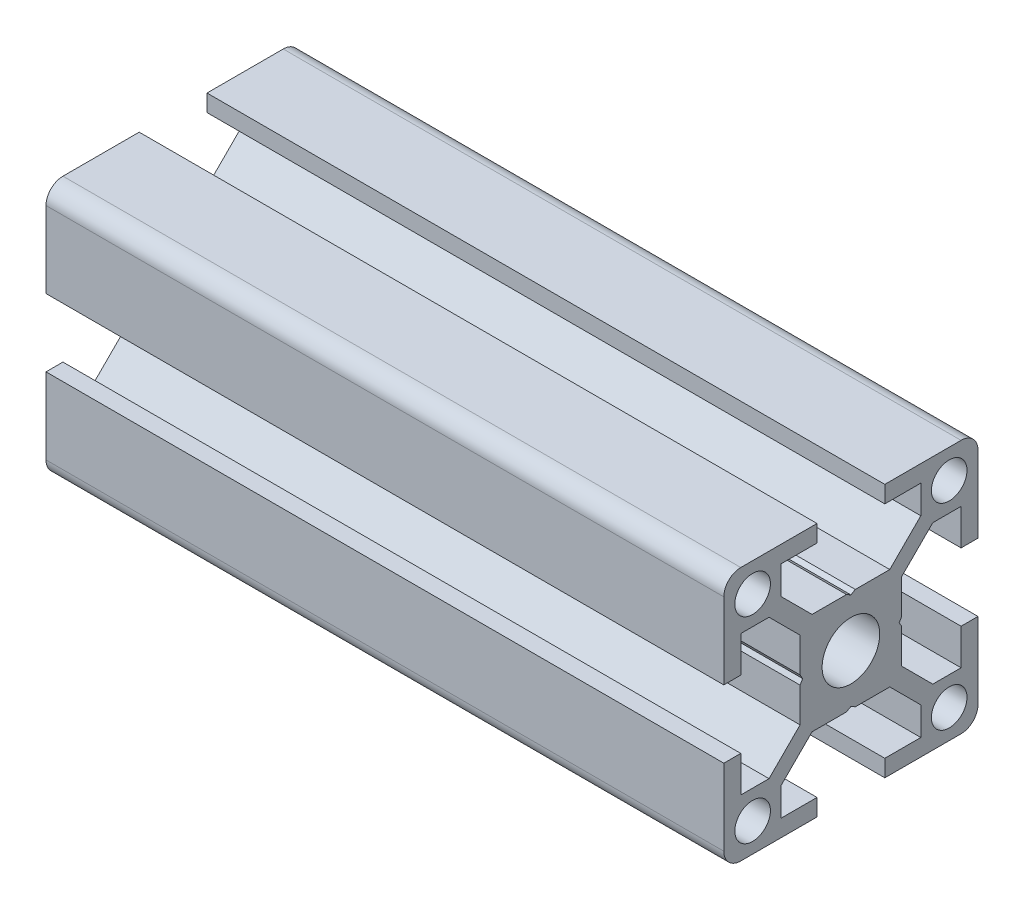
SolidWorks part; units mm, degrees
ref_plane "Front Plane" through (0, 0, 0) normal (0, 0, 1) x (1, 0, 0)
ref_plane "Top Plane" through (0, 0, 0) normal (0, 1, 0) x (1, 0, 0)
ref_plane "Right Plane" through (0, 0, 0) normal (1, 0, 0) x (0, 0, -1)
ref_plane "Plane1" through (0, 0, 0) normal (-1, 0, 0) x (0, -1, 0)
sketch "Sketch1" plane through (0, 0, 0) normal (-1, 0, 0) x (0, -1, 0)
  line L0 (13, -4) -> (13, -8.25)
  line L1 (13, -8.25) -> (9.6642, -8.25)
  line L2 (9.6642, -8.25) -> (6, -4.5858)
  line L3 (6, -4.5858) -> (6, -0.5196)
  line L4 (6, -0.5196) -> (5.7, 0)
  line L5 (5.7, 0) -> (6, 0.5196)
  line L6 (6, 0.5196) -> (6, 4.5858)
  line L7 (6, 4.5858) -> (9.6642, 8.25)
  line L8 (9.6642, 8.25) -> (13, 8.25)
  line L9 (13, 8.25) -> (13, 4)
  line L10 (13, 4) -> (15, 4)
  line L11 (15, 4) -> (15, 13)
  line L12 (13, 15) -> (4, 15)
  line L13 (4, 15) -> (4, 13)
  line L14 (4, 13) -> (8.25, 13)
  line L15 (8.25, 13) -> (8.25, 9.6642)
  line L16 (8.25, 9.6642) -> (4.5858, 6)
  line L17 (4.5858, 6) -> (0.5196, 6)
  line L18 (0.5196, 6) -> (0, 5.7)
  line L19 (0, 5.7) -> (-0.5196, 6)
  line L20 (-0.5196, 6) -> (-4.5858, 6)
  line L21 (-4.5858, 6) -> (-8.25, 9.6642)
  line L22 (-8.25, 9.6642) -> (-8.25, 13)
  line L23 (-8.25, 13) -> (-4, 13)
  line L24 (-4, 13) -> (-4, 15)
  line L25 (-4, 15) -> (-13, 15)
  line L26 (-15, 13) -> (-15, 4)
  line L27 (-15, 4) -> (-13, 4)
  line L28 (-13, 4) -> (-13, 8.25)
  line L29 (-13, 8.25) -> (-9.6642, 8.25)
  line L30 (-9.6642, 8.25) -> (-6, 4.5858)
  line L31 (-6, 4.5858) -> (-6, 0.5196)
  line L32 (-6, 0.5196) -> (-5.7, 0)
  line L33 (-5.7, 0) -> (-6, -0.5196)
  line L34 (-6, -0.5196) -> (-6, -4.5858)
  line L35 (-6, -4.5858) -> (-9.6642, -8.25)
  line L36 (-9.6642, -8.25) -> (-13, -8.25)
  line L37 (-13, -8.25) -> (-13, -4)
  line L38 (-13, -4) -> (-15, -4)
  line L39 (-15, -4) -> (-15, -13)
  line L40 (-13, -15) -> (-4, -15)
  line L41 (-4, -15) -> (-4, -13)
  line L42 (-4, -13) -> (-8.25, -13)
  line L43 (-8.25, -13) -> (-8.25, -9.6642)
  line L44 (-8.25, -9.6642) -> (-4.5858, -6)
  line L45 (-4.5858, -6) -> (-0.5196, -6)
  line L46 (-0.5196, -6) -> (0, -5.7)
  line L47 (0, -5.7) -> (0.5196, -6)
  line L48 (0.5196, -6) -> (4.5858, -6)
  line L49 (4.5858, -6) -> (8.25, -9.6642)
  line L50 (8.25, -9.6642) -> (8.25, -13)
  line L51 (8.25, -13) -> (4, -13)
  line L52 (4, -13) -> (4, -15)
  line L53 (4, -15) -> (13, -15)
  line L54 (15, -13) -> (15, -4)
  line L55 (15, -4) -> (13, -4)
  arc A0 (15, 13) -> (13, 15) centre (13, 13) ccw
  arc A1 (-13, 15) -> (-15, 13) centre (-13, 13) ccw
  arc A2 (-15, -13) -> (-13, -15) centre (-13, -13) ccw
  arc A3 (13, -15) -> (15, -13) centre (13, -13) ccw
  circle A4 centre (0, 0) radius 3.4
  circle A5 centre (11.6, -11.6) radius 2.1
  circle A6 centre (11.6, 11.6) radius 2.1
  circle A7 centre (-11.6, 11.6) radius 2.1
  circle A8 centre (-11.6, -11.6) radius 2.1
extrude "Boss-Extrude1" add sketch "Sketch1" against normal blind 80
